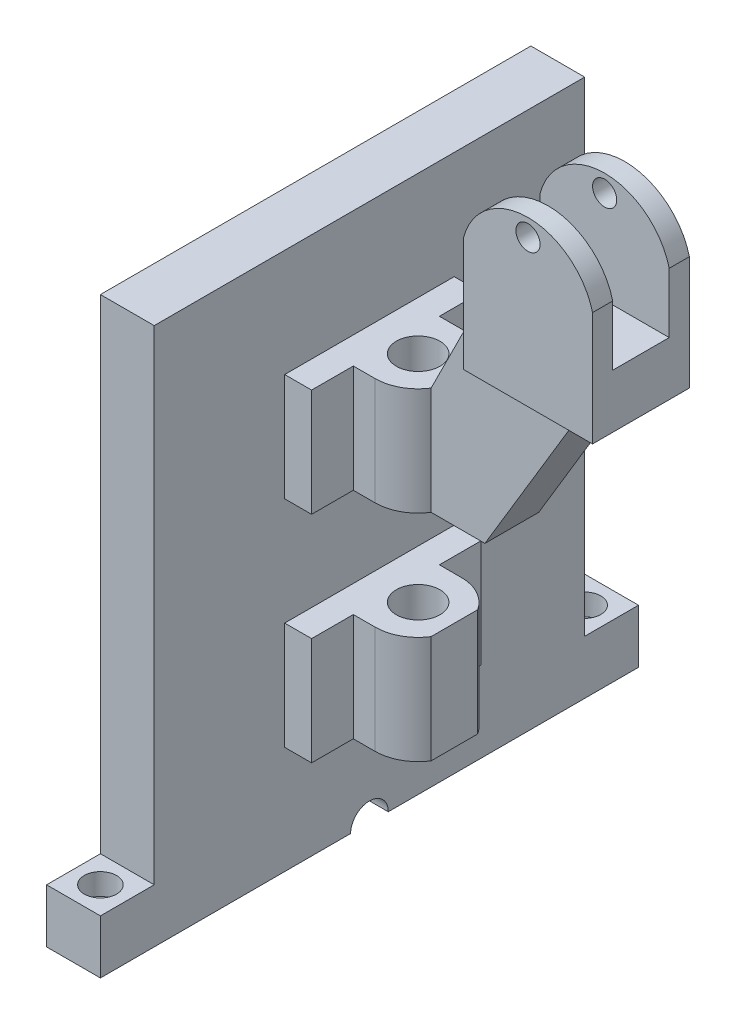
SolidWorks part; units mm, degrees
material "Gray Cast Iron"
ref_plane "Front Plane" through (0, 0, 0) normal (0, 0, 1) x (1, 0, 0)
ref_plane "Top Plane" through (0, 0, 0) normal (0, 1, 0) x (1, 0, 0)
ref_plane "Right Plane" through (0, 0, 0) normal (1, 0, 0) x (0, 0, -1)
sketch "Sketch1" plane through (0, 0, 0) normal (1, 0, 0) x (0, 0, -1)
  line L0 (-50, -50) -> (-3.5, -50)
  line L1 (-40, -50) -> (-3.5, -50)
  line L2 (-40, -50) -> (-40, 50)
  line L3 (-40, 50) -> (40, 50)
  line L4 (40, -50) -> (40, 50)
  line L5 (-40, -50) -> (40, 50) construction
  line L6 (-40, 50) -> (40, -50) construction
  line L8 (-50, -50) -> (-50, -40)
  line L9 (-50, -40) -> (-40, -40)
  line L10 (50, -50) -> (50, -40)
  line L11 (0, -50) -> (50, -40) construction
  line L12 (-50, -40) -> (0, -50) construction
  line L13 (40, -40) -> (50, -40)
  line L14 (3.5, -50) -> (50, -50)
  line L15 (3.5, -50) -> (40, -50)
  arc A0 (3.5, -50) -> (-3.5, -50) centre (0, -50) ccw
  point P0 (0, 0)
  point P6 (0, -50)
  dimension "D6" = 7
  dimension "D1" = 100
  dimension "D2" = 80
  dimension "D3" = 10
  dimension "D4" = 10
  dimension "D5" = 10
extrude "Boss-Extrude1" add sketch "Sketch1" along normal mid plane 10 contours A0 L14 L4 L3 L2 L0 | L9 L8 L0 L2 | L4 L14 L10 L13
sketch "Sketch4" plane through (0, -40, 0) normal (0, 1, 0) x (1, 0, 0)
  circle A0 centre (0, -45) radius 3
extrude "Cut-Extrude1" cut sketch "Sketch4" against normal blind 4
mirror "Mirror1" about plane through (0, 0, 0) normal (0, 0, 1) of "Cut-Extrude1"
sketch "Sketch5" plane through (0, 0, 0) normal (0, 1, 0) x (1, 0, 0)
  line L0 (5, 15.7517) -> (5, -15.7517)
  line L1 (5, -15.7517) -> (10, -15.7517)
  line L3 (5, 15.7517) -> (10, 15.7517)
  line L4 (10, -15.7517) -> (10, -8)
  line L5 (0, 0) -> (10, 15.7517) construction
  line L6 (0, 0) -> (10, -15.7517) construction
  line L7 (5, -40) -> (5, 40) construction
  line L8 (14.05, 8) -> (10, 8)
  line L9 (14.05, -8) -> (10, -8)
  line L10 (10, 8) -> (10, 15.7517)
  line L11 (20.7822, 4.3218) -> (20.7822, -4.3218)
  circle A0 centre (14.05, 0) radius 4.05
  arc A1 (14.05, -8) -> (20.7822, -4.3218) centre (14.05, 0) ccw
  arc A2 (20.7822, 4.3218) -> (14.05, 8) centre (14.05, 0) ccw
  point P0 (0, 0)
  dimension "D2" = 8.1
  dimension "D1" = 5
extrude "Boss-Extrude2" add sketch "Sketch5" along normal mid plane 60
sketch "Sketch6" plane through (0, 0, 40) normal (0, 0, 1) x (1, 0, 0)
  line L0 (5, 30) -> (5, -30) construction
  line L1 (5, 10) -> (31.3656, 10)
  line L3 (5, -10) -> (31.3656, -10)
  line L4 (31.3656, 10) -> (31.3656, -10)
  line L5 (5, 0) -> (31.3656, -10) construction
  line L6 (5, 0) -> (31.3656, 10) construction
  line L7 (5, 10) -> (5, -10)
  point P0 (5, 0)
  dimension "D1" = 10
  dimension "D2" = 10
extrude "Cut-Extrude2" cut sketch "Sketch6" against normal through all both and the other way through all
sketch "Sketch8" plane through (0, 10, 0) normal (0, -1, 0) x (1, 0, 0)
  line L1 (20.7822, 4.3218) -> (30.7822, 4.3218)
  line L2 (20.7822, 4.3218) -> (20.7822, -4.3218)
  line L3 (20.7822, -4.3218) -> (30.7822, -4.3218)
  line L4 (30.7822, 4.3218) -> (30.7822, -4.3218)
  dimension "D1" = 10
extrude "Boss-Extrude3" add sketch "Sketch8" against normal blind 40
sketch "Sketch9" plane through (0, 0, 4.3218) normal (0, 0, 1) x (1, 0, 0)
  line L0 (30.7822, 10) -> (54.7822, 50)
  arc A0 (54.7822, 50) -> (30.7822, 50) centre (42.7822, 50) ccw
  circle A1 centre (42.7822, 57.0674) radius 2.5
  line M4 (30.7822, 10) -> (30.7822, 50)
  dimension "D2" = 5
  dimension "D1" = 24
extrude "Boss-Extrude4" add sketch "Sketch9" against normal blind 10 contours L0 A0 A1 M4
sketch "Sketch10" plane through (0, 0, 4.3218) normal (0, 0, 1) x (1, 0, 0)
  line L0 (30.7822, 50) -> (20.7822, 30)
  line L1 (20.7822, 30) -> (20.7822, 50)
  line L2 (20.7822, 50) -> (30.7822, 50)
extrude "Cut-Extrude3" cut sketch "Sketch10" against normal through all both and the other way through all
ref_plane "Plane1" through (0, 0, -0.6782) normal (0, 0, 1) x (1, 0, 0)
sketch "Sketch11" plane through (0, 0, -0.6782) normal (0, 0, 1) x (1, 0, 0)
  line L1 (30.7822, 50) -> (58.0449, 50)
  line L2 (30.7822, 50) -> (30.7822, 64.7046)
  line L3 (30.7822, 64.7046) -> (58.0449, 64.7046)
  line L4 (58.0449, 50) -> (58.0449, 64.7046)
sketch "Sketch13" plane through (0, 0, 4.3218) normal (0, 0, 1) x (1, 0, 0)
  line L1 (58.0449, 64.7046) -> (30.7822, 64.7046)
  line L2 (58.0449, 64.7046) -> (58.0449, 50)
  line L3 (58.0449, 50) -> (30.7822, 50)
  line L4 (30.7822, 64.7046) -> (30.7822, 50)
extrude "Cut-Extrude5" cut sketch "Sketch13" against normal through all both and the other way through all
sketch "Sketch14" plane through (0, 50, 0) normal (0, 1, 0) x (1, 0, 0)
  line L0 (30.7822, 0.6782) -> (58.0449, 0.6782) construction
  line L1 (30.7822, -8.3218) -> (54.7822, -8.3218)
  line L2 (30.7822, -8.3218) -> (30.7822, 9.6782)
  line L3 (30.7822, 9.6782) -> (54.7822, 9.6782)
  line L4 (54.7822, -8.3218) -> (54.7822, 9.6782)
  line L5 (30.7822, -8.3218) -> (54.7822, 9.6782) construction
  line L6 (30.7822, 9.6782) -> (54.7822, -8.3218) construction
  point P0 (42.7822, 0.6782)
  dimension "D1" = 18
extrude "Boss-Extrude5" add sketch "Sketch14" against normal blind 10
sketch "Sketch15" plane through (0, 0, -0.6782) normal (0, 0, 1) x (1, 0, 0)
  line L0 (30.7822, 50) -> (30.7822, 64.7046) construction
  line L1 (30.7822, 50) -> (54.7822, 50)
  line L2 (30.7822, 50) -> (30.7822, 61.1541)
  line L4 (54.7822, 50) -> (54.7822, 61.15)
  arc A0 (54.7822, 61.15) -> (30.7822, 61.1541) centre (42.7817, 58.075) ccw
  circle A1 centre (42.7822, 67.2469) radius 2.2469
  dimension "D2" = 15
  dimension "D1" = 11.15
extrude "Boss-Extrude6" add sketch "Sketch15" against normal mid plane 18
sketch "Sketch16" plane through (0, 0, -0.6782) normal (0, 0, 1) x (1, 0, 0)
  line L1 (30.7822, 50) -> (57.6497, 50)
  line L2 (30.7822, 50) -> (30.7822, 72.4873)
  line L3 (30.7822, 72.4873) -> (57.6497, 72.4873)
  line L4 (57.6497, 50) -> (57.6497, 72.4873)
extrude "Cut-Extrude6" cut sketch "Sketch16" against normal mid plane 10.5
